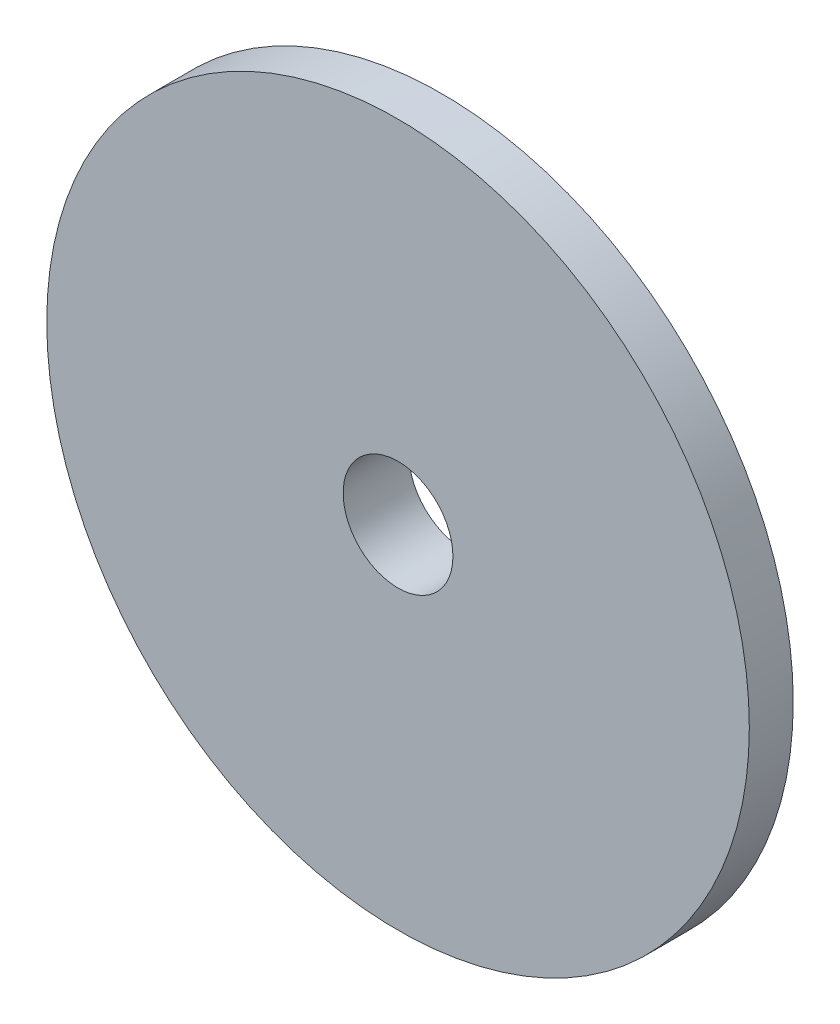
SolidWorks part; units mm, degrees
ref_plane "Front Plane" through (0, 0, 0) normal (0, 0, 1) x (1, 0, 0)
ref_plane "Top Plane" through (0, 0, 0) normal (0, 1, 0) x (1, 0, 0)
ref_plane "Right Plane" through (0, 0, 0) normal (1, 0, 0) x (0, 0, -1)
sketch "Sketch1" plane through (0, 0, 0) normal (0, 0, 1) x (1, 0, 0)
  circle A0 centre (0, 0) radius 19.95
  circle A1 centre (0, 0) radius 5
extrude "Spigot" add sketch "Sketch1" along normal blind 2
ref_plane "Plane_z2" through (0, 0, 2) normal (0, 0, 1) x (1, 0, 0)
sketch "Sketch2" plane through (0, 0, 2) normal (0, 0, 1) x (1, 0, 0)
  circle A0 centre (0, 0) radius 32
  circle A1 centre (0, 0) radius 5
extrude "Plate" add sketch "Sketch2" along normal blind 4
